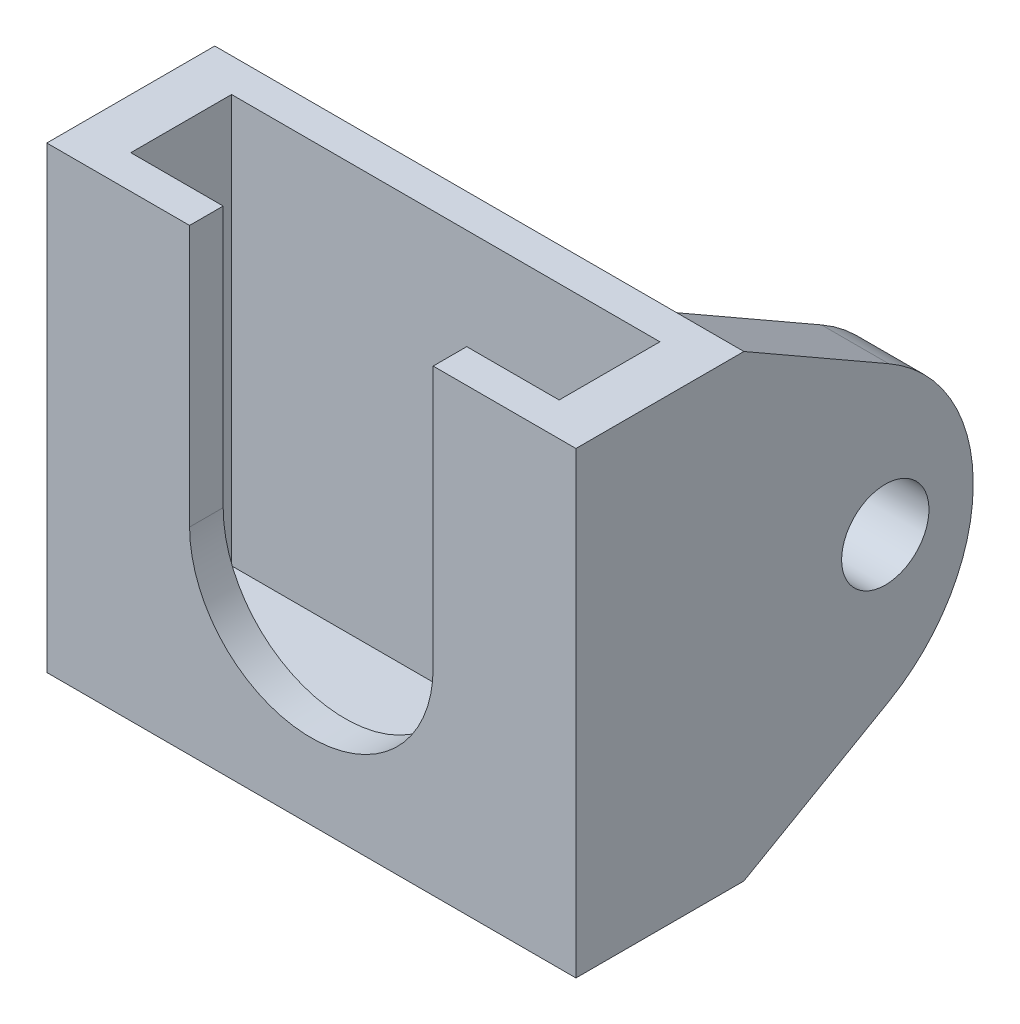
SolidWorks part; units mm, degrees
ref_plane "Front Plane" through (0, 0, 0) normal (0, 0, 1) x (1, 0, 0)
ref_plane "Top Plane" through (0, 0, 0) normal (0, 1, 0) x (1, 0, 0)
ref_plane "Right Plane" through (0, 0, 0) normal (1, 0, 0) x (0, 0, -1)
sketch "Sketch1" plane through (0, 0, 0) normal (0, 0, 1) x (1, 0, 0)
  line L0 (-3, -3) -> (-3, 27.3)
  line L1 (0, 0) -> (25.5, 0)
  line L2 (0, 0) -> (0, 24.3)
  line L3 (0, 24.3) -> (25.5, 24.3)
  line L4 (25.5, 0) -> (25.5, 24.3)
  line L5 (-3, 27.3) -> (28.5, 27.3)
  line L6 (28.5, -3) -> (28.5, 27.3)
  line L7 (-3, -3) -> (28.5, -3)
  dimension "D1" = 25.5
  dimension "D2" = 24.3
  dimension "D3" = 3
extrude "Boss-Extrude1" add sketch "Sketch1" along normal blind 6
sketch "Sketch2" plane through (0, 0, 0) normal (0, 0, -1) x (-1, 0, 0)
  line L1 (-28.5, 27.3) -> (3, 27.3)
  line L2 (-28.5, 27.3) -> (-28.5, -3)
  line L3 (-28.5, -3) -> (3, -3)
  line L4 (3, 27.3) -> (3, -3)
extrude "Boss-Extrude2" add sketch "Sketch2" along normal blind 2
sketch "Sketch3" plane through (0, 0, 6) normal (0, 0, 1) x (1, 0, 0)
  line L0 (-3, 27.3) -> (-3, -3) construction
  line L2 (-3, 24.392) -> (-3, 27.3)
  line L3 (-3, 27.3) -> (28.5, 27.3)
  line L4 (28.5, 24.392) -> (28.5, 27.3)
  line L5 (0, 24.3) -> (-3, 24.3)
  line L6 (-3, 24.3) -> (-3, 24.392)
  line L7 (0, 24.3) -> (28.5, 24.3)
  line L8 (28.5, -3) -> (28.5, 27.3) construction
  line L9 (28.5, 24.3) -> (28.5, 24.392)
extrude "Cut-Extrude1" cut sketch "Sketch3" against normal blind 61
sketch "Sketch4" plane through (0, 0, 6) normal (0, 0, 1) x (1, 0, 0)
  line L0 (12.75, 0) -> (12.75, 16) construction
  line L1 (-3, 24.3) -> (5.5, 24.3)
  line L2 (-3, 24.3) -> (-3, -3)
  line L3 (-3, -3) -> (28.5, -3)
  line L4 (28.5, 24.3) -> (28.5, -3)
  line L5 (0, 0) -> (25.5, 0) construction
  line L6 (5.5, 8.75) -> (5.5, 24.3)
  line L7 (20, 8.75) -> (20, 24.3)
  line L8 (20, 24.3) -> (28.5, 24.3)
  arc A0 (5.5, 8.75) -> (20, 8.75) centre (12.75, 8.75) ccw
  dimension "D1" = 14.5
  dimension "D2" = 16
extrude "Boss-Extrude3" add sketch "Sketch4" along normal blind 2
sketch "Sketch5" plane through (0, 0, -2) normal (0, 0, -1) x (-1, 0, 0)
  line L0 (-28.5, -3) -> (3, -3) construction
  line L1 (-28.5, 24.3) -> (-24.5, 24.3)
  line L2 (-28.5, 24.3) -> (-28.5, -3)
  line L3 (-28.5, -3) -> (-24.5, -3)
  line L4 (-24.5, 24.3) -> (-24.5, -3)
  dimension "D1" = 4
extrude "Boss-Extrude4" add sketch "Sketch5" along normal blind 38
sketch "Sketch6" plane through (24.5, 0, 0) normal (-1, 0, 0) x (0, 0, 1)
  line L0 (-2, -3) -> (-40, -3)
  line L2 (-2, -3) -> (-2, 24.3) construction
  line L3 (-2, 24.3) -> (-17.8264, 15.2339)
  line L4 (-17.8264, 6.0661) -> (-2, -3)
  line L5 (-18.8323, 13.4984) -> (-18.8323, 7.8016)
  line L6 (-18.8323, 10.65) -> (-2, 10.65) construction
  line L7 (-40, -3) -> (-40, 24.3)
  line L8 (-40, 24.3) -> (-2, 24.3)
  arc A0 (-18.8323, 7.8016) -> (-17.8264, 6.0661) centre (-16.8323, 7.8016) ccw
  arc A1 (-18.8323, 13.4984) -> (-17.8264, 15.2339) centre (-16.8323, 13.4984) cw
  dimension "D1" = 2
extrude "Cut-Extrude2" cut sketch "Sketch6" against normal blind 38
sketch "Sketch7" plane through (24.5, 0, 0) normal (-1, 0, 0) x (0, 0, 1)
  line L0 (-18.8323, 10.65) -> (-2, 10.65) construction
  line L1 (-18.8323, 7.8016) -> (-18.8323, 13.4984) construction
  line L2 (-2, -3) -> (-2, 24.3) construction
  circle A0 centre (-10.4161, 10.65) radius 2.6
  dimension "D1" = 5.2
extrude "Cut-Extrude3" cut sketch "Sketch7" against normal blind 38
sketch "Sketch8" plane through (24.5, 0, 0) normal (-1, 0, 0) x (0, 0, 1)
  line L0 (-6.5317, 23.5258) -> (-21.1373, 18.3853)
  line L1 (-21.1373, 18.3853) -> (-20.6718, 0.7661)
  line L2 (-20.6718, 0.7661) -> (-11.2527, 0.6145)
  arc A0 (-2, -3) -> (-2, 24.3) centre (-2, 10.65) cw
  arc M2 (-18.8323, 7.8016) -> (-17.8264, 6.0661) centre (-16.8323, 7.8016) ccw
  line M3 (-17.8264, 6.0661) -> (-2, -3)
  line M5 (-2, 24.3) -> (-17.8264, 15.2339)
  arc M6 (-17.8264, 15.2339) -> (-18.8323, 13.4984) centre (-16.8323, 13.4984) ccw
  line M7 (-18.8323, 13.4984) -> (-18.8323, 7.8016)
extrude "Cut-Extrude4" cut sketch "Sketch8" against normal blind 38 contours A0 M3 M5 M6 M7 M2
fillet "Fillet1" radius 10 2 edges at (26.5, 3.7452, -13.7748) (26.5, 17.5548, -13.7748)
